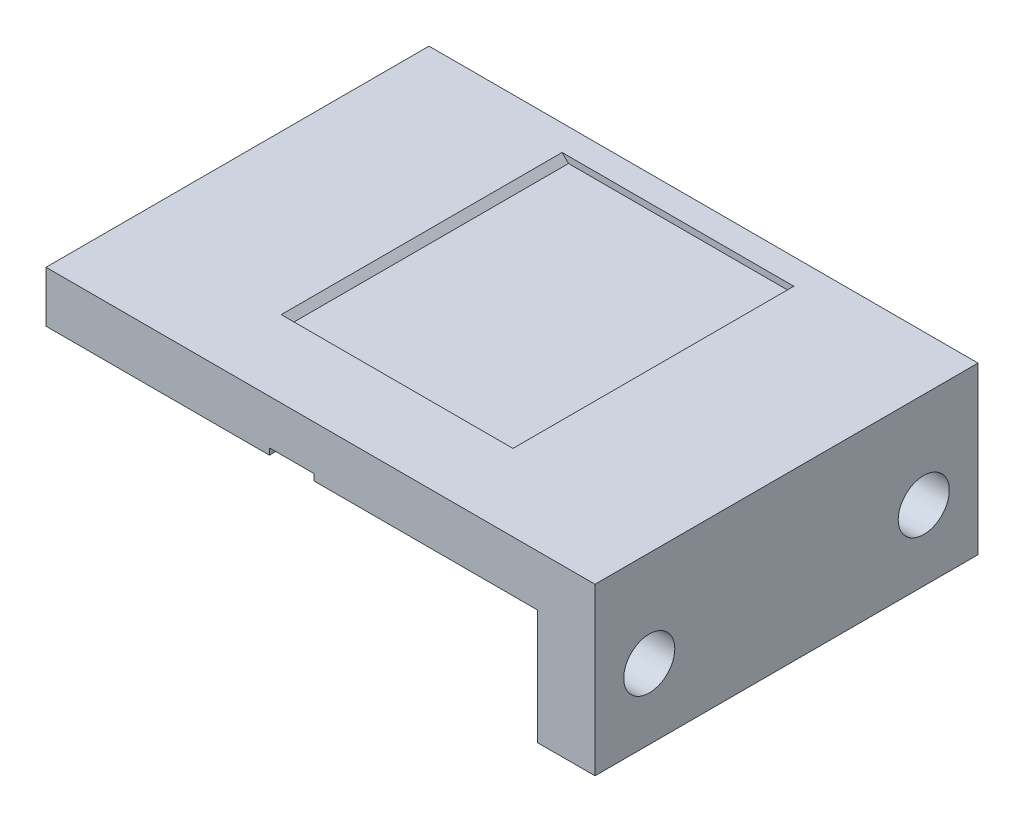
SolidWorks part; units mm, degrees
ref_plane "Front Plane" through (0, 0, 0) normal (0, 0, 1) x (1, 0, 0)
ref_plane "Top Plane" through (0, 0, 0) normal (0, 1, 0) x (1, 0, 0)
ref_plane "Right Plane" through (0, 0, 0) normal (1, 0, 0) x (0, 0, -1)
sketch "Sketch1" plane through (0, 0, 0) normal (0, 1, 0) x (1, 0, 0)
  line L1 (0, 0) -> (77, 0)
  line L2 (0, 0) -> (0, 60)
  line L3 (0, 60) -> (77, 60)
  line L4 (77, 0) -> (77, 60)
  dimension "D1" = 77
  dimension "D2" = 60
extrude "Boss-Extrude1" add sketch "Sketch1" along normal blind 8
sketch "Sketch3" plane through (77, 0, 0) normal (1, 0, 0) x (0, 0, -1)
  line L0 (60, 8) -> (60, 0) construction
  line L1 (0, 8) -> (60, 8)
  line L2 (0, 8) -> (0, -18)
  line L3 (0, -18) -> (60, -18)
  line L4 (60, 8) -> (60, -18)
  dimension "D1" = 26
extrude "Boss-Extrude2" add sketch "Sketch3" along normal blind 9 contours L2 L3 L4 L1
sketch "Sketch4" plane through (86, 0, 0) normal (1, 0, 0) x (0, 0, -1)
  line L0 (0, 8) -> (60, 8) construction
  line L1 (30, 8) -> (30, -18) construction
  line L2 (0, -18) -> (60, -18) construction
  line L5 (0, 8) -> (0, -18) construction
  line L6 (17, -7) -> (0, -7) construction
  circle A0 centre (8.5, -7) radius 4
  circle A2 centre (51.5, -7) radius 4
  point P12 (8.5, -7)
  point P18 (8.5, -7)
  dimension "D1" = 8
  dimension "D2" = 15
  dimension "D3" = 21.5
extrude "Cut-Extrude2" cut sketch "Sketch4" against normal through all
sketch "Sketch5" plane through (0, 8, 0) normal (0, 1, 0) x (1, 0, 0)
  line L0 (86, 60) -> (0, 60) construction
  line L1 (25.85, 12) -> (60.15, 12)
  line L2 (25.85, 12) -> (25.85, 56)
  line L3 (25.85, 56) -> (60.15, 56)
  line L4 (60.15, 12) -> (60.15, 56)
  point P4 (43, 56)
  point P7 (43, 60)
  dimension "D1" = 44
  dimension "D2" = 34.3
  dimension "D3" = 4
extrude "recess" cut sketch "Sketch5" against normal blind 1 contours L1 L4 L3 L2
sketch "Sketch6" plane through (0, 0, -56) normal (0, 0, 1) x (1, 0, 0)
  line L0 (25.85, 7) -> (24.85, 8)
  line L1 (25.85, 8) -> (60.15, 8) construction
  line L2 (25.85, 7) -> (25.85, 8) construction
  line L3 (24.85, 8) -> (25.85, 8)
  line L4 (25.85, 8) -> (25.85, 7)
  line L5 (43, 8) -> (43, 7) construction
  line L6 (25.85, 7) -> (60.15, 7) construction
  line L7 (60.15, 8) -> (60.15, 7)
  line L8 (61.15, 8) -> (60.15, 8)
  line L9 (60.15, 7) -> (61.15, 8)
  dimension "D1" = 45
extrude "Angles in recess" cut sketch "Sketch6" along normal up to surface (44 mm away) up to face at (43, 7.5, -12)
ref_plane "Plane1" through (0, 0, -30) normal (0, 0, 1) x (1, 0, 0)
sketch "Sketch7" plane through (0, 0, 0) normal (0, -1, 0) x (1, 0, 0)
  line L0 (77, -60) -> (0, -60) construction
  line L1 (42, -60) -> (35, -60)
  line L2 (42, -60) -> (42, 0)
  line L3 (42, 0) -> (35, 0)
  line L4 (35, -60) -> (35, 0)
  line L5 (0, 0) -> (77, 0) construction
  point P8 (38.5, -60)
  point P9 (38.5, -60)
  dimension "D1" = 7
extrude "where the belt go" cut sketch "Sketch7" against normal blind 1
